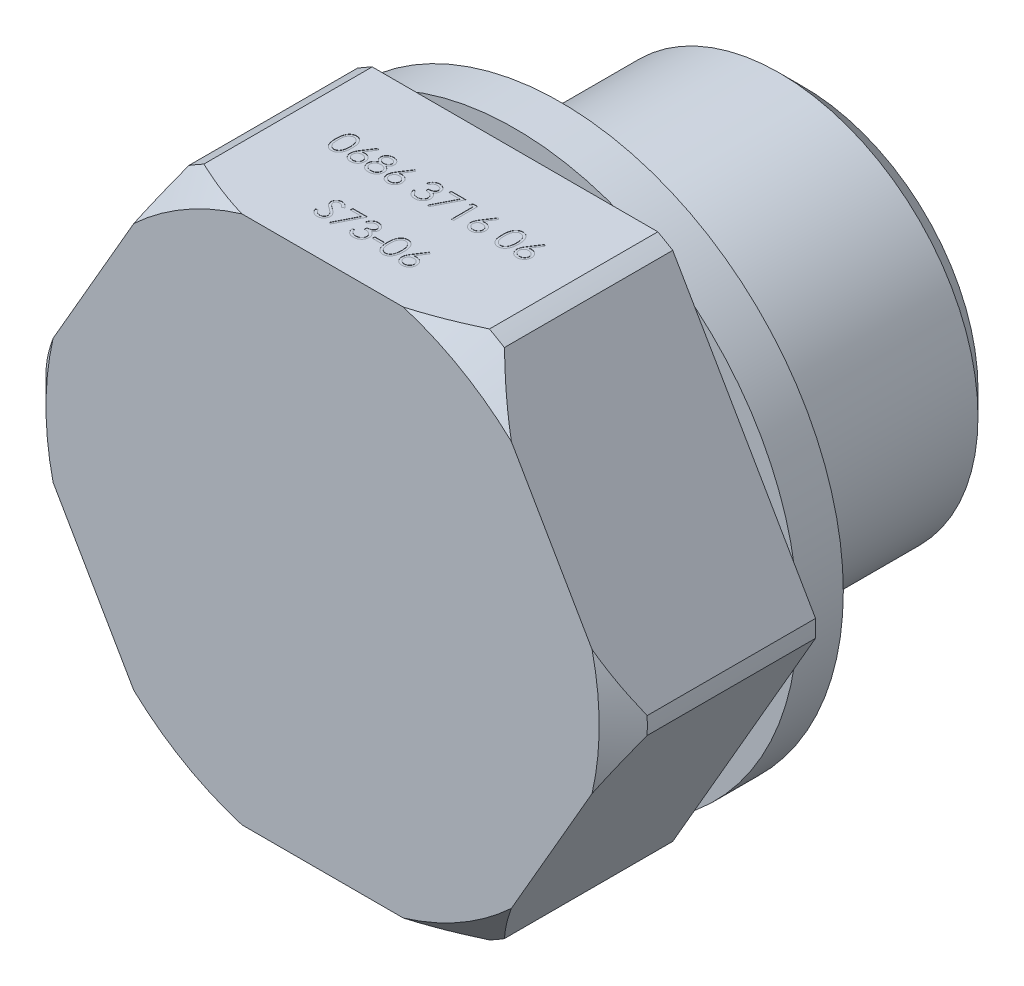
SolidWorks part; units mm, degrees
ref_plane "Front Plane" through (0, 0, 0) normal (0, 0, 1) x (1, 0, 0)
ref_plane "Top Plane" through (0, 0, 0) normal (0, 1, 0) x (1, 0, 0)
ref_plane "Right Plane" through (0, 0, 0) normal (1, 0, 0) x (0, 0, -1)
sketch "Sketch1" plane through (0, 0, 0) normal (1, 0, 0) x (0, 0, -1)
  line L0 (0, 0) -> (14.66, 0) construction
  line L1 (0, 0) -> (0, 11.5)
  line L2 (1, 12.5) -> (8, 12.5)
  line L3 (8, 12.5) -> (8, 7.25)
  line L4 (10, 8.25) -> (19, 8.25)
  line L5 (19, 8.25) -> (20, 7.25)
  line L6 (20, 7.25) -> (20, 6)
  line L7 (0, 0) -> (12.5, 0)
  line L8 (10, 8.25) -> (10, 7.25)
  line L9 (10, 7.25) -> (8, 7.25)
  line L10 (0, 11.5) -> (1, 12.5)
  line L11 (20, 6) -> (17.2, 4.5)
  line L12 (17.2, 4.5) -> (15.2039, 4.5)
  line L13 (15.2039, 4.5) -> (12.5, 0)
  point P4 (0, 12.5)
  dimension "D1" = 16.5
  dimension "D2" = 14.5
  dimension "D3" = 45
  dimension "D4" = 12
  dimension "D5" = 20
  dimension "D6" = 25
  dimension "D7" = 2
  dimension "D8" = 14.5
  dimension "D9" = 12
  dimension "D10" = 9
  dimension "D12" = 59
  dimension "D13" = 7.5
  dimension "D14" = 2.8
revolve "Revolve1" add sketch "Sketch1" angle 360 about L0
cosmetic thread "Cosmetic Thread1" parameters "D2"=14.5
sketch "Sketch2" plane through (0, 0, 0) normal (0, 0, 1) x (1, 0, 0)
  line L1 (-6.3509, 11) -> (-12.7017, 0)
  line L2 (-12.7017, 0) -> (-6.3509, -11)
  line L3 (-6.3509, -11) -> (6.3509, -11)
  line L4 (6.3509, -11) -> (12.7017, 0)
  line L5 (12.7017, 0) -> (6.3509, 11)
  line L6 (6.3509, 11) -> (-6.3509, 11)
  circle A0 centre (0, 0) radius 11 construction
  dimension "D1" = 22
extrude "Extrude1" cut sketch "Sketch2" against normal blind 10 flip side to cut
sketch "Sketch3" plane through (0, 0, 0) normal (1, 0, 0) x (0, 0, -1)
  line L0 (0, 0) -> (26.0658, 0) construction
  line L1 (8, 0.3583) -> (8, 10.6417) construction
  line L2 (8, 11.75) -> (9.9, 11.75)
  line L3 (8, 11.75) -> (8, 9.75)
  line L4 (8, 9.75) -> (9.9, 9.75)
  line L5 (9.9, 11.75) -> (9.9, 9.75)
  dimension "D1" = 23.5
  dimension "D2" = 19.5
  dimension "D3" = 1.9
revolve "Revolve2" add sketch "Sketch3" angle 360 about L0
sketch "Sketch4" plane through (0, 0, 0) normal (1, 0, 0) x (0, 0, -1)
  line L0 (0, 0) -> (23.3802, 0) construction
  line L1 (8, 10.6417) -> (8, 0.3583) construction
  circle A0 centre (9.2, 8.4) radius 1.2
  dimension "D1" = 16.8
  dimension "D2" = 2.4
  dimension "D3" = 1.2
revolve "Revolve3" add sketch "Sketch4" angle 360 about L0
sketch "Sketch5" plane through (0, 11, 0) normal (0, 1, 0) x (1, 0, 0)
  line L0 (-5.2993, 4.1651) -> (5.4585, 4.1651) construction
  text T0 "0686 3716 06\r\nS73-06" font "Century Gothic" height 1
extrude "Cut-Extrude1" cut sketch "Sketch5" against normal blind 0.01
